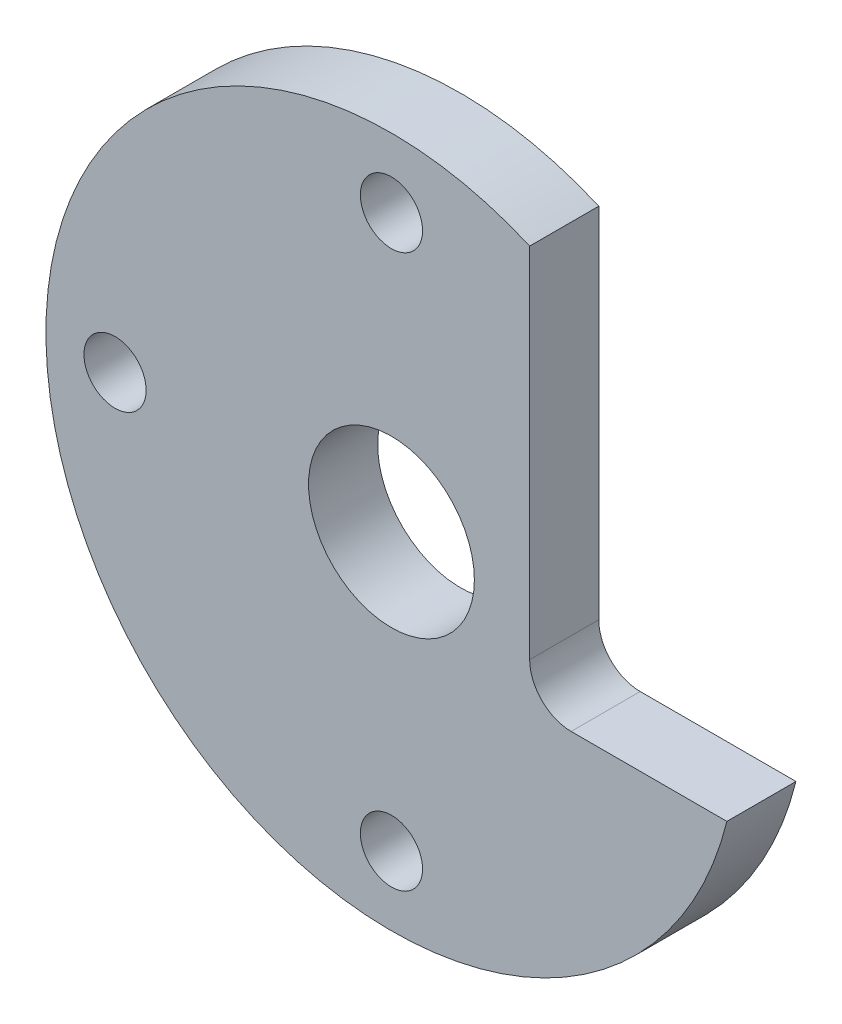
SolidWorks part; units mm, degrees
ref_plane "Ebene vorne" through (0, 0, 0) normal (0, 0, 1) x (1, 0, 0)
ref_plane "Ebene oben" through (0, 0, 0) normal (0, 1, 0) x (1, 0, 0)
ref_plane "Ebene rechts" through (0, 0, 0) normal (1, 0, 0) x (0, 0, -1)
sketch "Skizze1" plane through (0, 0, 0) normal (0, 0, 1) x (1, 0, 0)
  line L0 (-39.014, 0) -> (0, 0) construction
  line L1 (0, 0) -> (0, -31.0448) construction
  line L2 (0, -31.0448) -> (0, 33.2355) construction
  circle A0 centre (0, 0) radius 6
  circle A1 centre (0, 0) radius 25
  circle A2 centre (0, 0) radius 20 construction
  circle A3 centre (0, 20) radius 2.25
  circle A4 centre (-20, 0) radius 2.25
  circle A5 centre (0, -20) radius 2.25
extrude "Aufsatz-Linear austragen1" add sketch "Skizze1" along normal blind 5
sketch "Skizze2" plane through (0, 0, 0) normal (0, 0, -1) x (-1, 0, 0)
  line L0 (-10, 33.3512) -> (-10, -6)
  line L1 (-10, -6) -> (-34.327, -6)
  line L2 (-34.327, -6) -> (-34.327, 33.3512)
  line L3 (-34.327, 33.3512) -> (-10, 33.3512)
  circle A0 centre (0, 0) radius 6 construction
  dimension "D2" = 10
  dimension "D3" = 6
  dimension "D1" = 39.3512
extrude "Schnitt-Linear austragen1" cut sketch "Skizze2" against normal blind 5
fillet "Verrundung1" radius 3 1 edges at (10, -6, 2.5)
